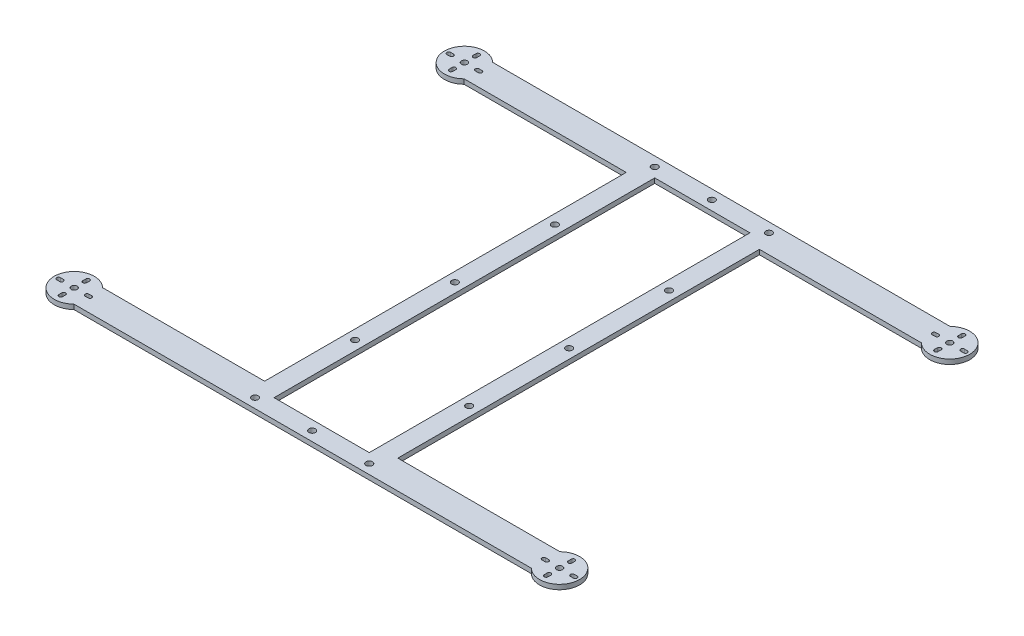
SolidWorks part; units mm, degrees
ref_plane "Front Plane" through (0, 0, 0) normal (0, 0, 1) x (1, 0, 0)
ref_plane "Top Plane" through (0, 0, 0) normal (0, 1, 0) x (1, 0, 0)
ref_plane "Right Plane" through (0, 0, 0) normal (1, 0, 0) x (0, 0, -1)
sketch "Sketch1" plane through (0, 0, 0) normal (0, 1, 0) x (1, 0, 0)
  line L1 (-44.45, 139.7) -> (44.45, 139.7)
  line L2 (-44.45, 120.65) -> (-44.45, -120.65)
  line L3 (-44.45, -139.7) -> (44.45, -139.7)
  line L4 (44.45, 120.65) -> (44.45, -120.65)
  line L5 (44.45, 139.7) -> (161.925, 139.7)
  line L7 (44.45, 120.65) -> (161.925, 120.65)
  line L8 (161.925, 139.7) -> (161.925, 120.65)
  line L14 (0, 0) -> (0, 187.5455) construction
  line L17 (0, 0) -> (-239.6804, 0) construction
  line L21 (0, 0) -> (44.45, 0) construction
  line L22 (-44.45, 120.65) -> (-161.925, 120.65)
  line L23 (-44.45, 139.7) -> (-161.925, 139.7)
  line L24 (-161.925, 139.7) -> (-161.925, 120.65)
  line L37 (-31.75, 127) -> (31.75, 127)
  line L40 (-31.75, 127) -> (-31.75, -127)
  line L43 (-31.75, -127) -> (31.75, -127)
  line L46 (31.75, 127) -> (31.75, -127)
  line L49 (44.45, -120.65) -> (161.925, -120.65)
  line L50 (44.45, -139.7) -> (161.925, -139.7)
  line L51 (161.925, -139.7) -> (161.925, -120.65)
  line L88 (-161.925, -139.7) -> (-161.925, -120.65)
  line L89 (-44.45, -139.7) -> (-161.925, -139.7)
  line L90 (-44.45, -120.65) -> (-161.925, -120.65)
  point P4 (0, 139.7)
  point P6 (-44.45, 0)
  dimension "D4" = 117.475
  dimension "D1" = 279.4
  dimension "D2" = 88.9
  dimension "D3" = 19.05
  dimension "D6" = 12.7
  dimension "D7" = 12.7
  dimension "D8" = 12.7
  dimension "D10" = 117.475
  dimension "D12" = 12.7
  dimension "D18" = 19.05
extrude "Boss-Extrude1" add sketch "Sketch1" along normal blind 3.175
sketch "Sketch4" plane through (0, 3.175, 0) normal (0, 1, 0) x (1, 0, 0)
  line L0 (161.925, 120.65) -> (161.925, 139.7) construction
  line L1 (-161.925, 139.7) -> (-161.925, 120.65) construction
  line L2 (-161.925, -120.65) -> (-161.925, -139.7) construction
  line L3 (161.925, -139.7) -> (161.925, -120.65) construction
  circle A0 centre (161.925, 130.175) radius 13.335
  circle A1 centre (-161.925, 130.175) radius 13.335
  circle A2 centre (-161.925, -130.175) radius 13.335
  circle A3 centre (161.925, -130.175) radius 13.335
  point P18 (161.925, -130.175)
extrude "Boss-Extrude4" add sketch "Sketch4" against normal up to surface (3.175 mm away) up to face at (0, 0, 0)
sketch "Sketch5" plane through (0, 3.175, 0) normal (0, 1, 0) x (1, 0, 0)
  line L0 (151.425, 130.175) -> (153.425, 130.175) construction
  line L1 (151.425, 131.425) -> (153.425, 131.425)
  line L2 (151.425, 128.925) -> (153.425, 128.925)
  line L3 (161.925, 130.175) -> (161.925, 143.51) construction
  line L4 (172.425, 130.175) -> (170.425, 130.175) construction
  line L5 (172.425, 131.425) -> (170.425, 131.425)
  line L6 (172.425, 128.925) -> (170.425, 128.925)
  line L7 (161.925, 139.175) -> (161.925, 137.175) construction
  line L8 (163.175, 139.175) -> (163.175, 137.175)
  line L9 (160.675, 139.175) -> (160.675, 137.175)
  line L10 (161.925, 130.175) -> (175.26, 130.175) construction
  line L11 (161.925, 121.175) -> (161.925, 123.175) construction
  line L12 (163.175, 121.175) -> (163.175, 123.175)
  line L13 (160.675, 121.175) -> (160.675, 123.175)
  line L14 (0, 0) -> (0, 263.0018) construction
  line L15 (0, 0) -> (558.7896, 0) construction
  line L16 (-151.425, 130.175) -> (-153.425, 130.175) construction
  line L17 (-151.425, 131.425) -> (-153.425, 131.425)
  line L18 (-151.425, 128.925) -> (-153.425, 128.925)
  line L19 (-172.425, 130.175) -> (-170.425, 130.175) construction
  line L20 (-172.425, 131.425) -> (-170.425, 131.425)
  line L21 (-172.425, 128.925) -> (-170.425, 128.925)
  line L22 (-161.925, 139.175) -> (-161.925, 137.175) construction
  line L23 (-163.175, 139.175) -> (-163.175, 137.175)
  line L24 (-160.675, 139.175) -> (-160.675, 137.175)
  line L25 (-161.925, 121.175) -> (-161.925, 123.175) construction
  line L26 (-163.175, 121.175) -> (-163.175, 123.175)
  line L27 (-160.675, 121.175) -> (-160.675, 123.175)
  line L28 (-161.925, 130.175) -> (-175.26, 130.175) construction
  line L29 (-161.925, 130.175) -> (-161.925, 143.51) construction
  line L30 (151.425, -130.175) -> (153.425, -130.175) construction
  line L31 (151.425, -131.425) -> (153.425, -131.425)
  line L32 (151.425, -128.925) -> (153.425, -128.925)
  line L33 (161.925, -139.175) -> (161.925, -137.175) construction
  line L34 (163.175, -139.175) -> (163.175, -137.175)
  line L35 (160.675, -139.175) -> (160.675, -137.175)
  line L36 (172.425, -130.175) -> (170.425, -130.175) construction
  line L37 (172.425, -131.425) -> (170.425, -131.425)
  line L38 (172.425, -128.925) -> (170.425, -128.925)
  line L39 (161.925, -121.175) -> (161.925, -123.175) construction
  line L40 (163.175, -121.175) -> (163.175, -123.175)
  line L41 (160.675, -121.175) -> (160.675, -123.175)
  line L42 (161.925, -130.175) -> (175.26, -130.175) construction
  line L43 (161.925, -130.175) -> (161.925, -143.51) construction
  line L44 (-161.925, -130.175) -> (-161.925, -143.51) construction
  line L45 (-161.925, -130.175) -> (-175.26, -130.175) construction
  line L46 (-161.925, -121.175) -> (-161.925, -123.175) construction
  line L47 (-163.175, -121.175) -> (-163.175, -123.175)
  line L48 (-160.675, -121.175) -> (-160.675, -123.175)
  line L49 (-161.925, -139.175) -> (-161.925, -137.175) construction
  line L50 (-163.175, -139.175) -> (-163.175, -137.175)
  line L51 (-160.675, -139.175) -> (-160.675, -137.175)
  line L52 (-172.425, -130.175) -> (-170.425, -130.175) construction
  line L53 (-172.425, -131.425) -> (-170.425, -131.425)
  line L54 (-172.425, -128.925) -> (-170.425, -128.925)
  line L55 (-151.425, -130.175) -> (-153.425, -130.175) construction
  line L56 (-151.425, -131.425) -> (-153.425, -131.425)
  line L57 (-151.425, -128.925) -> (-153.425, -128.925)
  circle A0 centre (161.925, 130.175) radius 2
  arc A1 (151.425, 131.425) -> (151.425, 128.925) centre (151.425, 130.175) ccw
  arc A2 (153.425, 128.925) -> (153.425, 131.425) centre (153.425, 130.175) ccw
  arc A3 (152.5924, 120.65) -> (152.5924, 139.7) centre (161.925, 130.175) ccw construction
  arc A4 (172.425, 131.425) -> (172.425, 128.925) centre (172.425, 130.175) cw
  arc A5 (170.425, 128.925) -> (170.425, 131.425) centre (170.425, 130.175) cw
  arc A6 (163.175, 139.175) -> (160.675, 139.175) centre (161.925, 139.175) ccw
  arc A7 (160.675, 137.175) -> (163.175, 137.175) centre (161.925, 137.175) ccw
  arc A8 (163.175, 121.175) -> (160.675, 121.175) centre (161.925, 121.175) cw
  arc A9 (160.675, 123.175) -> (163.175, 123.175) centre (161.925, 123.175) cw
  arc A10 (-151.425, 131.425) -> (-151.425, 128.925) centre (-151.425, 130.175) cw
  arc A11 (-153.425, 128.925) -> (-153.425, 131.425) centre (-153.425, 130.175) cw
  arc A12 (-172.425, 131.425) -> (-172.425, 128.925) centre (-172.425, 130.175) ccw
  arc A13 (-170.425, 128.925) -> (-170.425, 131.425) centre (-170.425, 130.175) ccw
  arc A14 (-163.175, 139.175) -> (-160.675, 139.175) centre (-161.925, 139.175) cw
  arc A15 (-160.675, 137.175) -> (-163.175, 137.175) centre (-161.925, 137.175) cw
  arc A16 (-163.175, 121.175) -> (-160.675, 121.175) centre (-161.925, 121.175) ccw
  arc A17 (-160.675, 123.175) -> (-163.175, 123.175) centre (-161.925, 123.175) ccw
  circle A18 centre (-161.925, 130.175) radius 2
  arc A19 (151.425, -131.425) -> (151.425, -128.925) centre (151.425, -130.175) cw
  arc A20 (153.425, -128.925) -> (153.425, -131.425) centre (153.425, -130.175) cw
  arc A21 (163.175, -139.175) -> (160.675, -139.175) centre (161.925, -139.175) cw
  arc A22 (160.675, -137.175) -> (163.175, -137.175) centre (161.925, -137.175) cw
  arc A23 (172.425, -131.425) -> (172.425, -128.925) centre (172.425, -130.175) ccw
  arc A24 (170.425, -128.925) -> (170.425, -131.425) centre (170.425, -130.175) ccw
  arc A25 (163.175, -121.175) -> (160.675, -121.175) centre (161.925, -121.175) ccw
  arc A26 (160.675, -123.175) -> (163.175, -123.175) centre (161.925, -123.175) ccw
  circle A27 centre (161.925, -130.175) radius 2
  circle A28 centre (-161.925, -130.175) radius 2
  arc A29 (-163.175, -121.175) -> (-160.675, -121.175) centre (-161.925, -121.175) cw
  arc A30 (-160.675, -123.175) -> (-163.175, -123.175) centre (-161.925, -123.175) cw
  arc A31 (-163.175, -139.175) -> (-160.675, -139.175) centre (-161.925, -139.175) ccw
  arc A32 (-160.675, -137.175) -> (-163.175, -137.175) centre (-161.925, -137.175) ccw
  arc A33 (-172.425, -131.425) -> (-172.425, -128.925) centre (-172.425, -130.175) cw
  arc A34 (-170.425, -128.925) -> (-170.425, -131.425) centre (-170.425, -130.175) cw
  arc A35 (-151.425, -131.425) -> (-151.425, -128.925) centre (-151.425, -130.175) ccw
  arc A36 (-153.425, -128.925) -> (-153.425, -131.425) centre (-153.425, -130.175) ccw
  point P5 (152.425, 130.175)
  point P16 (171.425, 130.175)
  point P23 (161.925, 138.175)
  point P31 (161.925, 122.175)
  point P42 (-152.425, 130.175)
  point P49 (-171.425, 130.175)
  point P56 (-161.925, 138.175)
  point P63 (-161.925, 122.175)
  point P74 (152.425, -130.175)
  point P81 (161.925, -138.175)
  point P88 (171.425, -130.175)
  point P95 (161.925, -122.175)
  point P110 (-161.925, -122.175)
  point P117 (-161.925, -138.175)
  point P124 (-171.425, -130.175)
  point P131 (-152.425, -130.175)
  dimension "D1" = 4
  dimension "D2" = 2.5
  dimension "D3" = 2
  dimension "D4" = 9.5
  dimension "D5" = 2.5
  dimension "D6" = 2
  dimension "D7" = 8
extrude "Motor Holes" cut sketch "Sketch5" against normal through all
sketch "Sketch7" plane through (0, 3.175, 0) normal (0, 1, 0) x (1, 0, 0)
  line L0 (152.5924, 139.7) -> (-152.5924, 139.7) construction
  line L1 (-44.45, 120.65) -> (-44.45, -120.65) construction
  line L2 (0, 0) -> (0, 246.0772) construction
  line L3 (0, 0) -> (301.4392, 0) construction
  circle A0 centre (-38.1, 133.35) radius 2.159
  circle A1 centre (-38.1, 66.675) radius 2.159
  circle A2 centre (-38.1, 0) radius 2.159
  circle A3 centre (-38.1, -66.675) radius 2.159
  circle A5 centre (-38.1, -133.35) radius 2.159
  circle A6 centre (38.1, -133.35) radius 2.159
  circle A7 centre (38.1, -66.675) radius 2.159
  circle A8 centre (38.1, 0) radius 2.159
  circle A9 centre (38.1, 66.675) radius 2.159
  circle A10 centre (38.1, 133.35) radius 2.159
  circle A11 centre (0, 133.35) radius 2.159
  circle A12 centre (0, -133.35) radius 2.159
  dimension "D1" = 4.318
  dimension "D2" = 6.35
  dimension "D3" = 6.35
  dimension "D4" = 66.675
  dimension "D5" = 66.675
  dimension "D6" = 66.675
  dimension "D7" = 66.675
extrude "Cut-Extrude2" cut sketch "Sketch7" against normal through all
